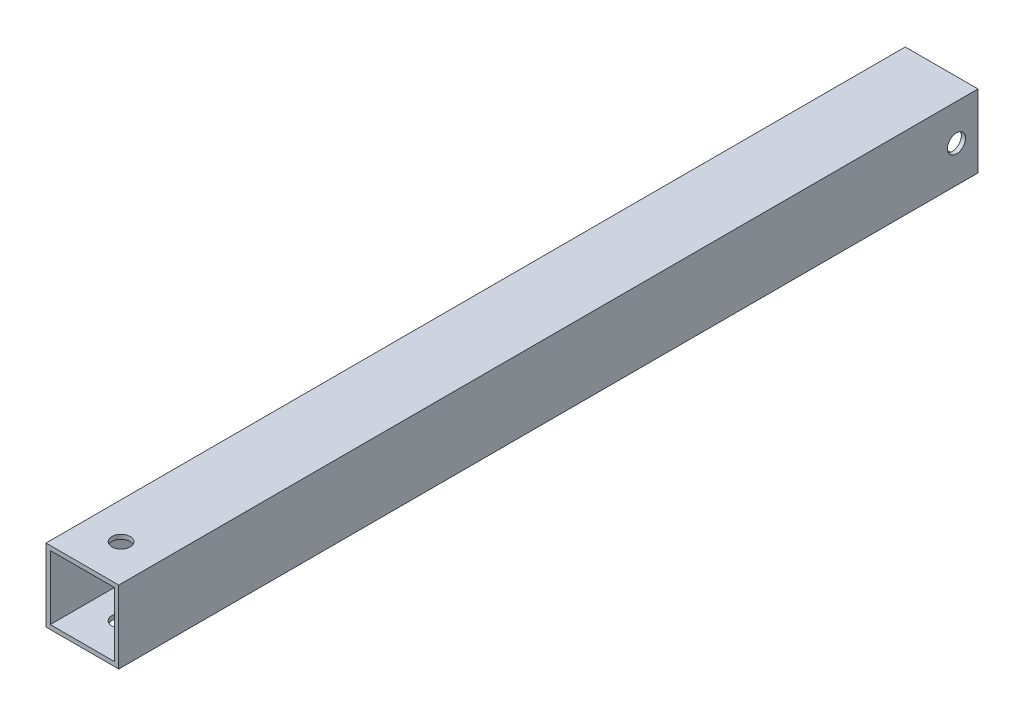
SolidWorks part; units mm, degrees
material "AISI 1020 Acero laminado en frío"
ref_plane "Alzado" through (0, 0, 0) normal (0, 0, 1) x (1, 0, 0)
ref_plane "Planta" through (0, 0, 0) normal (0, 1, 0) x (1, 0, 0)
ref_plane "Vista lateral" through (0, 0, 0) normal (1, 0, 0) x (0, 0, -1)
sketch "Croquis1" plane through (0, 0, 0) normal (0, 0, 1) x (1, 0, 0)
  line L0 (-22.4, 22.4) -> (22.4, 22.4)
  line L1 (-25.4, -25.4) -> (25.4, -25.4)
  line L2 (-25.4, -25.4) -> (-25.4, 25.4)
  line L3 (-25.4, 25.4) -> (25.4, 25.4)
  line L4 (25.4, -25.4) -> (25.4, 25.4)
  line L5 (-25.4, -25.4) -> (25.4, 25.4) construction
  line L6 (-25.4, 25.4) -> (25.4, -25.4) construction
  line L7 (22.4, -22.4) -> (22.4, 22.4)
  line L8 (-22.4, -22.4) -> (22.4, -22.4)
  line L9 (-22.4, -22.4) -> (-22.4, 22.4)
  point P0 (0, 0)
  dimension "D1" = 50.8
  dimension "D2" = 50.8
  dimension "D3" = 3
extrude "Saliente-Extruir1" add sketch "Croquis1" along normal mid plane 600
sketch "Croquis2" plane through (25.4, 0, 0) normal (1, 0, 0) x (0, 0, -1)
  line L0 (-300, 0) -> (300, 0) construction
  line L1 (-300, -25.4) -> (-300, 25.4) construction
  line L2 (300, -25.4) -> (300, 25.4) construction
  line L3 (-300, -25.4) -> (300, -25.4) construction
  line L5 (-300, 25.4) -> (300, 25.4) construction
  line L6 (0, 25.4) -> (0, -25.4) construction
  circle A1 centre (285, 0) radius 6.35
  point P18 (-300, 0)
  dimension "D1" = 12.7
  dimension "D4" = 15
extrude "Cortar-Extruir1" cut sketch "Croquis2" against normal through all
sketch "Croquis3" plane through (0, 25.4, 0) normal (0, 1, 0) x (1, 0, 0)
  line L0 (44.2746, -273) -> (-44.1968, -273) construction
  line L1 (25.4, -300) -> (-25.4, -300) construction
  line L2 (0, -300) -> (0, -192.0651) construction
  circle A0 centre (0, -273) radius 6.35
  dimension "D1" = 12.7
  dimension "D2" = 27
extrude "Cortar-Extruir2" cut sketch "Croquis3" against normal blind 70
